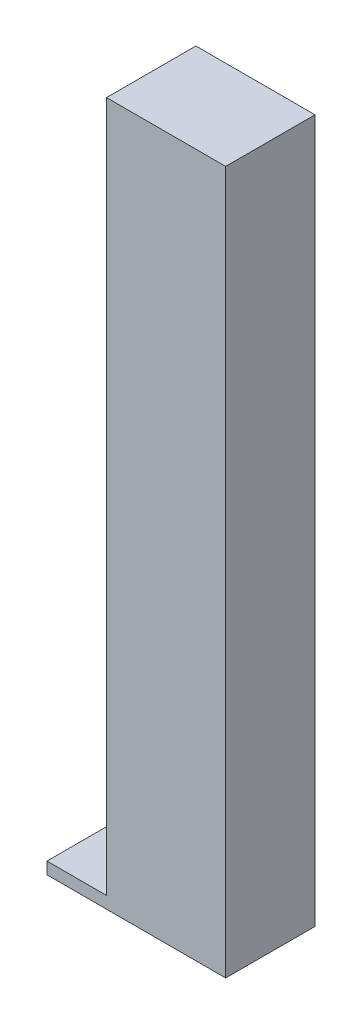
SolidWorks part; units mm, degrees
ref_plane "Front Plane" through (0, 0, 0) normal (0, 0, 1) x (1, 0, 0)
ref_plane "Top Plane" through (0, 0, 0) normal (0, 1, 0) x (1, 0, 0)
ref_plane "Right Plane" through (0, 0, 0) normal (1, 0, 0) x (0, 0, -1)
sketch "Sketch2" plane through (0, 0, 0) normal (0, 1, 0) x (1, 0, 0)
  line L0 (-10, 4.9267) -> (-10, 0.9267)
  line L1 (-10, -10.0733) -> (10, -10.0733)
  line L2 (-10, -10.0733) -> (-10, -6.0733)
  line L3 (-10, 4.9267) -> (10, 4.9267)
  line L4 (10, -10.0733) -> (10, 4.9267)
  line L5 (-10, -6.0733) -> (-7, -6.0733)
  line L6 (-7, -6.0733) -> (-7, -8.0733)
  line L7 (-7, -8.0733) -> (0, -8.0733)
  line L8 (0, -8.0733) -> (0, -9.0733)
  line L9 (0, -9.0733) -> (1, -9.0733)
  line L10 (1, -9.0733) -> (1, -8.0733)
  line L11 (1, -8.0733) -> (8, -8.0733)
  line L12 (8, -8.0733) -> (8, 2.9267)
  line L13 (0, 2.9267) -> (0, 3.9267)
  line L14 (0, 3.9267) -> (1, 3.9267)
  line L15 (1, 3.9267) -> (1, 2.9267)
  line L16 (1, 2.9267) -> (8, 2.9267)
  line L17 (-7, 2.9267) -> (0, 2.9267)
  line L18 (-7, 2.9267) -> (-7, 0.9267)
  line L19 (-7, 0.9267) -> (-10, 0.9267)
  point P0 (0, 0)
  dimension "D1" = 20
  dimension "D2" = 3
  dimension "D3" = 15
  dimension "D4" = 20
  dimension "D5" = 4
  dimension "D6" = 4
extrude "Boss-Extrude1" add sketch "Sketch2" along normal blind 115
ref_plane "Plane1" through (0, 115, 0) normal (0, 1, 0) x (1, 0, 0)
sketch "Sketch3" plane through (0, 115, 0) normal (0, 1, 0) x (1, 0, 0)
  line L1 (-10, -10.0733) -> (10, -10.0733)
  line L2 (-10, -10.0733) -> (-10, 4.9267)
  line L3 (-10, 4.9267) -> (10, 4.9267)
  line L4 (10, -10.0733) -> (10, 4.9267)
extrude "Boss-Extrude2" add sketch "Sketch3" along normal blind 1
ref_plane "Plane2" through (0, 0, 0) normal (0, -1, 0) x (-1, 0, 0)
sketch "Sketch7" plane through (0, 0, 0) normal (0, -1, 0) x (-1, 0, 0)
  line L1 (-10, 4.9267) -> (20, 4.9267)
  line L2 (-10, 4.9267) -> (-10, -10.0733)
  line L3 (-10, -10.0733) -> (20, -10.0733)
  line L4 (20, 4.9267) -> (20, -10.0733)
extrude "Boss-Extrude5" add sketch "Sketch7" along normal blind 2
ref_plane "Plane3" through (0, 0, 0) normal (0, 1, 0) x (1, 0, 0)
sketch "Sketch8" plane through (0, 0, 0) normal (0, 1, 0) x (1, 0, 0)
  line L0 (-10, 0.9267) -> (-10, -2.5733)
  line L1 (-10, -2.5733) -> (-10, -6.0733)
sketch "Sketch9" plane through (0, 0, 0) normal (0, 1, 0) x (1, 0, 0)
  line L1 (-20, 4.9267) -> (-10, 4.9267) construction
  line L2 (-11, 4.9267) -> (-11, -2.5733)
  line L3 (-11, -2.5733) -> (-11, -10.0733)
  line L4 (-10, -10.0733) -> (-20, -10.0733) construction
